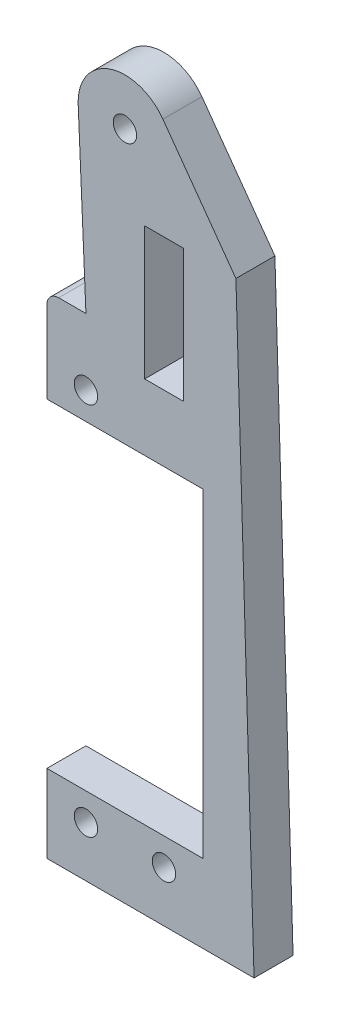
SolidWorks part; units mm, degrees
ref_plane "Plan de face" through (0, 0, 0) normal (0, 0, 1) x (1, 0, 0)
ref_plane "Plan de dessus" through (0, 0, 0) normal (0, 1, 0) x (1, 0, 0)
ref_plane "Plan de droite" through (0, 0, 0) normal (1, 0, 0) x (0, 0, -1)
sketch "Esquisse1" plane through (0, 0, 0) normal (0, 0, 1) x (1, 0, 0)
  line L0 (0, 10) -> (0, 0)
  line L1 (0, 0) -> (26.5541, 0)
  line L2 (10, 10) -> (10, 51) construction
  line L3 (0, 63) -> (5, 63)
  line L4 (12.5289, 76.5) -> (12.5289, 59.5)
  line L5 (11, 51) -> (0, 51)
  line L6 (12.5289, 76.5) -> (17.5289, 76.5)
  line L7 (20, 10) -> (11, 10)
  line L8 (0, 30.5) -> (0, 10)
  line L9 (0, 30.5) -> (20, 30.5) construction
  line L10 (20, 10) -> (20, 51)
  line L11 (20, 51) -> (11, 51)
  line L12 (14.8704, 89.5041) -> (24.2264, 76.5)
  line L13 (24.2264, 76.5) -> (26.5541, 0)
  line L14 (12.5289, 59.5) -> (17.5289, 59.5)
  line L15 (17.5289, 59.5) -> (17.5289, 76.5)
  line L16 (4.0057, 85.7379) -> (5, 63)
  line L18 (11, 10) -> (0, 10)
  line L25 (0, 63) -> (0, 51)
  line L26 (17.5289, 76.5) -> (24.2264, 76.5) construction
  circle A0 centre (5, 54.5) radius 1.5
  circle A1 centre (15, 54.5) radius 1.5 construction
  circle A2 centre (15, 6.5) radius 1.5
  circle A3 centre (5, 6.5) radius 1.5
  circle A4 centre (10, 86) radius 1.5
  arc A6 (4.0057, 85.7379) -> (14.8704, 89.5041) centre (10, 86) cw
  circle A7 centre (10, 86) radius 1.5 construction
  dimension "D6" = 20
  dimension "D8" = 5
  dimension "D11" = 3
  dimension "D16" = 10
  dimension "D5" = 3
  dimension "D12" = 91.743
  dimension "D13" = 6
  dimension "D1" = 41
  dimension "D2" = 12
  dimension "D3" = 3.5
  dimension "D4" = 5
  dimension "D7" = 5
  dimension "D9" = 5
  dimension "D10" = 17
extrude "Boss.-Extru.1" add sketch "Esquisse1" along normal blind 5
fillet "Congé3" radius 1.5 1 edges at (0, 63, 2.5)
